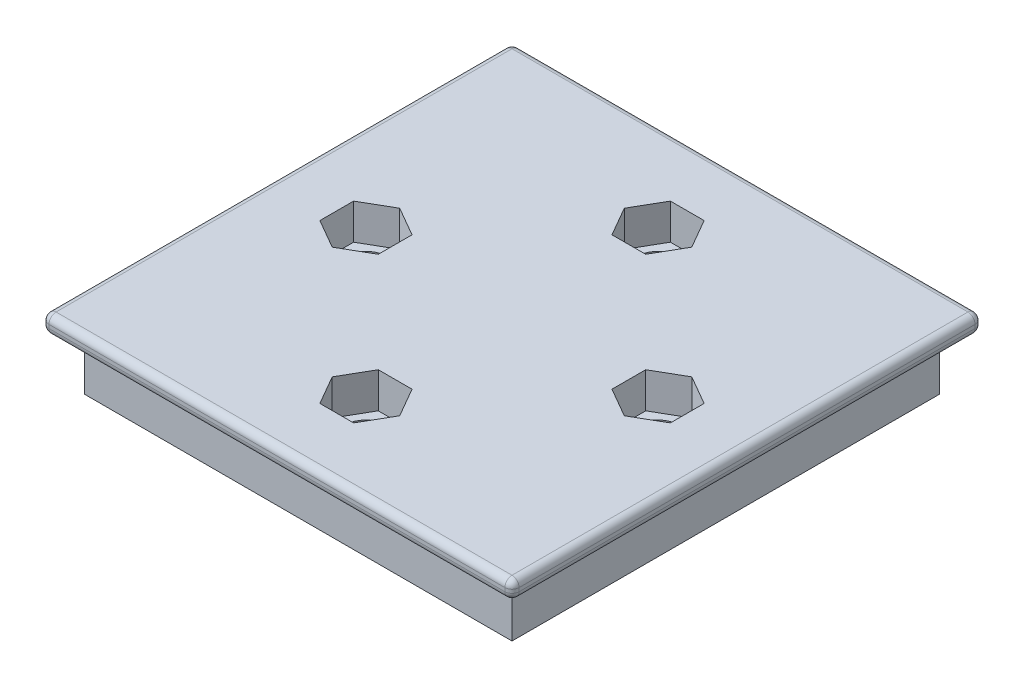
SolidWorks part; units mm, degrees
ref_plane "Front Plane" through (0, 0, 0) normal (0, 0, 1) x (1, 0, 0)
ref_plane "Top Plane" through (0, 0, 0) normal (0, 1, 0) x (1, 0, 0)
ref_plane "Right Plane" through (0, 0, 0) normal (1, 0, 0) x (0, 0, -1)
sketch "Sketch1" plane through (0, 0, 0) normal (0, 1, 0) x (1, 0, 0)
  line L1 (30, 30) -> (-30, 30)
  line L2 (30, 30) -> (30, -30)
  line L3 (30, -30) -> (-30, -30)
  line L4 (-30, 30) -> (-30, -30)
  line L5 (30, 30) -> (-30, -30) construction
  line L6 (30, -30) -> (-30, 30) construction
  circle A0 centre (0, 20.5) radius 3
  circle A1 centre (20.5, 0) radius 3
  circle A2 centre (0, -20.5) radius 3
  circle A3 centre (-20.5, 0) radius 3
  point P0 (0, 0)
  point P14 (-20.5, 0)
  point P15 (0, 0)
  point P16 (0, 0)
  point P17 (0, 0)
  point P18 (0, 0)
  point P19 (0, 0)
  dimension "D3" = 6
  dimension "D4" = 6
  dimension "D5" = 6
  dimension "D6" = 6
  dimension "D1" = 60
  dimension "D2" = 60
  dimension "D7" = 41
  dimension "D8" = 41
  dimension "D9" = 20.5
  dimension "D10" = 20.5
extrude "Boss-Extrude1" add sketch "Sketch1" along normal blind 10
sketch "Sketch2" plane through (0, 10, 0) normal (0, 1, 0) x (1, 0, 0)
  line L11 (30, 30) -> (-30, 30)
  line L12 (30, 30) -> (30, -30)
  line L13 (30, -30) -> (-30, -30)
  line L14 (33, 33) -> (-33, 33)
  line L15 (33, -33) -> (33, 33)
  line L16 (-33, -33) -> (33, -33)
  line L17 (-33, 33) -> (-33, -33)
  line L18 (33, 33) -> (-33, 33)
  line L19 (33, -33) -> (33, 33)
  line L20 (-33, -33) -> (33, -33)
  line L21 (-33, 33) -> (-33, -33)
  line L22 (-30, 30) -> (-30, -30)
  line L23 (30, 30) -> (-30, -30) construction
  line L24 (30, -30) -> (-30, 30) construction
  point P0 (0, 0)
  dimension "D1" = 3
extrude "Boss-Extrude2" add sketch "Sketch2" against normal blind 2.5 contours L18 L21 L20 L19
sketch "Sketch3" plane through (0, 10, 0) normal (0, 1, 0) x (1, 0, 0)
  line L0 (-4.7343, 20.5) -> (-2.3671, 16.4)
  line L1 (-20.5, -4.7343) -> (-16.4, -2.3671)
  line L2 (-16.4, -2.3671) -> (-16.4, 2.3671)
  line L3 (-16.4, 2.3671) -> (-20.5, 4.7343)
  line L4 (-20.5, 4.7343) -> (-24.6, 2.3671)
  line L5 (-24.6, 2.3671) -> (-24.6, -2.3671)
  line L6 (-24.6, -2.3671) -> (-20.5, -4.7343)
  line L7 (-2.3671, 16.4) -> (2.3671, 16.4)
  line L8 (2.3671, 16.4) -> (4.7343, 20.5)
  line L9 (4.7343, 20.5) -> (2.3671, 24.6)
  line L10 (2.3671, 24.6) -> (-2.3671, 24.6)
  line L11 (-2.3671, 24.6) -> (-4.7343, 20.5)
  line L12 (20.5, 4.7343) -> (16.4, 2.3671)
  line L13 (16.4, 2.3671) -> (16.4, -2.3671)
  line L14 (16.4, -2.3671) -> (20.5, -4.7343)
  line L15 (20.5, -4.7343) -> (24.6, -2.3671)
  line L16 (24.6, -2.3671) -> (24.6, 2.3671)
  line L17 (24.6, 2.3671) -> (20.5, 4.7343)
  line L18 (4.7343, -20.5) -> (2.3671, -16.4)
  line L19 (2.3671, -16.4) -> (-2.3671, -16.4)
  line L20 (-2.3671, -16.4) -> (-4.7343, -20.5)
  line L21 (-4.7343, -20.5) -> (-2.3671, -24.6)
  line L22 (-2.3671, -24.6) -> (2.3671, -24.6)
  line L23 (2.3671, -24.6) -> (4.7343, -20.5)
  circle A0 centre (-20.5, 0) radius 4.1 construction
  point P1 (0, 0)
  point P10 (0, 0)
  point P11 (0, 0)
  point P30 (0, 0)
  point P31 (-0.6467, -21.5862)
  point P32 (24.483, -2.3671)
  point P33 (0, -16.4)
  point P34 (0, 0)
  dimension "D1" = 8.2
  dimension "D2" = 4
extrude "Cut-Extrude1" cut sketch "Sketch3" against normal blind 5
fillet "Fillet1" radius 1 12 edges at (0, 7.5, 33) (0, 10, 33) (-33, 8.75, 33) (-33, 7.5, 0) (-33, 10, 0) (-33, 8.75, -33) (0, 7.5, -33) (0, 10, -33) (33, 8.75, -33) (33, 7.5, 0) (33, 8.75, 33) (33, 10, 0)
